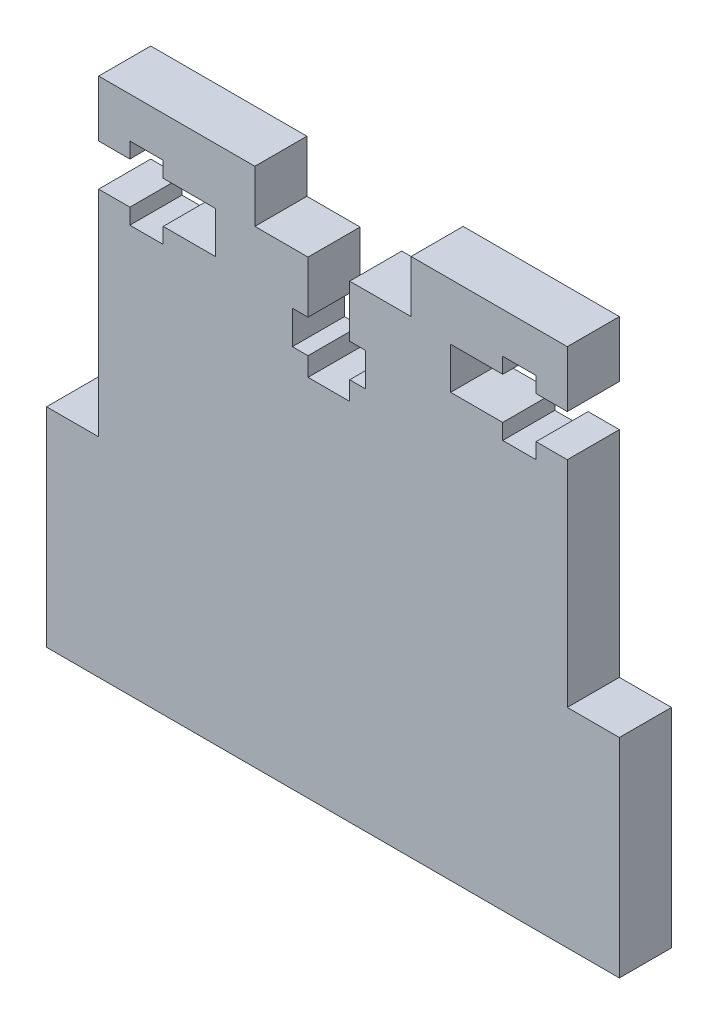
SolidWorks part; units mm, degrees
ref_plane "Front Plane" through (0, 0, 0) normal (0, 0, 1) x (1, 0, 0)
ref_plane "Top Plane" through (0, 0, 0) normal (0, 1, 0) x (1, 0, 0)
ref_plane "Right Plane" through (0, 0, 0) normal (1, 0, 0) x (0, 0, -1)
sketch "Sketch1" plane through (0, 0, 0) normal (0, 0, 1) x (1, 0, 0)
  line L1 (-30, 25) -> (15, 25)
  line L2 (-30, 25) -> (-30, -25)
  line L3 (-30, -25) -> (15, -25)
  line L4 (15, 25) -> (15, -25)
  dimension "D1" = 45
  dimension "D2" = 50
  dimension "D3" = 30
  dimension "D4" = 25
extrude "Boss-Extrude1" add sketch "Sketch1" along normal blind 5
sketch "Sketch5" plane through (0, 0, 5) normal (0, 0, 1) x (1, 0, 0)
  line L14 (-30, 17.6) -> (-13.6039, 17.6) construction
  line L26 (0, 0) -> (-23.656, 0) construction
  line L27 (0, 0) -> (0, 19.5594) construction
  line L28 (-30, 15.6) -> (-30, 19.6)
  line L64 (15, 19.6) -> (12, 19.6)
  line L65 (-27, 15.6) -> (-30, 15.6)
  line L66 (-27, 14.1) -> (-27, 15.6)
  line L67 (-23.8, 14.1) -> (-27, 14.1)
  line L68 (-23.8, 15.6) -> (-23.8, 14.1)
  line L69 (-18.8, 15.6) -> (-23.8, 15.6)
  line L70 (-18.8, 19.6) -> (-18.8, 15.6)
  line L71 (-23.8, 19.6) -> (-18.8, 19.6)
  line L72 (-23.8, 21.1) -> (-23.8, 19.6)
  line L73 (-27, 21.1) -> (-23.8, 21.1)
  line L74 (-27, 19.6) -> (-27, 21.1)
  line L75 (-30, 19.6) -> (-27, 19.6)
  line L78 (15, -25) -> (15, 25) construction
  line L79 (12, 19.6) -> (12, 21.1)
  line L80 (12, 21.1) -> (8.8, 21.1)
  line L81 (8.8, 21.1) -> (8.8, 19.6)
  line L82 (8.8, 19.6) -> (3.8, 19.6)
  line L83 (3.8, 19.6) -> (3.8, 15.6)
  line L84 (3.8, 15.6) -> (8.8, 15.6)
  line L85 (8.8, 15.6) -> (8.8, 14.1)
  line L86 (8.8, 14.1) -> (12, 14.1)
  line L87 (12, 14.1) -> (12, 15.6)
  line L88 (12, 15.6) -> (15, 15.6)
  line L89 (15, 15.6) -> (15, 19.6)
  line L90 (3.8, 17.6) -> (15, 17.6) construction
  dimension "D1" = 4
  dimension "D2" = 2
  dimension "D3" = 1.5
  dimension "D4" = 1.5
  dimension "D5" = 3
  dimension "D6" = 3.2
  dimension "D7" = 5
  dimension "D8" = 3
  dimension "D9" = 3.2
  dimension "D10" = 5
extrude "Cut-Extrude1" cut sketch "Sketch5" against normal blind 5
sketch "Sketch6" plane through (0, 0, 0) normal (0, 0, -1) x (-1, 0, 0)
  line L0 (0, -25) -> (0, 34.8388) construction
  line L1 (-15, -25) -> (-20, -25)
  line L2 (-15, -25) -> (-15, -5)
  line L3 (-15, -5) -> (-20, -5)
  line L4 (-20, -25) -> (-20, -5)
  line L7 (30, -25) -> (35, -25)
  line L8 (30, -25) -> (30, -5)
  line L9 (30, -5) -> (35, -5)
  line L10 (35, -25) -> (35, -5)
  dimension "D1" = 20
  dimension "D2" = 5
  dimension "D3" = 5
  dimension "D4" = 20
extrude "Boss-Extrude2" add sketch "Sketch6" against normal blind 5
sketch "Sketch7" plane through (0, 0, 5) normal (0, 0, 1) x (1, 0, 0)
  line L0 (15, 25) -> (-30, 25) construction
  line L1 (-15, 25) -> (0, 25)
  line L2 (-15, 25) -> (-15, 20)
  line L3 (-15, 20) -> (0, 20)
  line L4 (0, 25) -> (0, 20)
  line L5 (-30, 25) -> (-30, 19.6) construction
  dimension "D1" = 15
  dimension "D2" = 15
  dimension "D3" = 5
extrude "Cut-Extrude2" cut sketch "Sketch7" against normal blind 10
sketch "Sketch8" plane through (0, 0, 5) normal (0, 0, 1) x (1, 0, 0)
  line L0 (-9.8947, 20) -> (-9.8947, 15)
  line L1 (-15, 20) -> (0, 20) construction
  line L2 (-9.8947, 10) -> (-5.8947, 10)
  line L3 (-5.8947, 10) -> (-5.8947, 11.8)
  line L4 (-9.8947, 20) -> (-5.8947, 20)
  line L5 (-9.8947, 15) -> (-11.3947, 15)
  line L6 (-11.3947, 15) -> (-11.3947, 11.8)
  line L7 (-11.3947, 11.8) -> (-9.8947, 11.8)
  line L8 (-9.8947, 11.8) -> (-9.8947, 10)
  line L9 (-5.8947, 15) -> (-4.3947, 15)
  line L10 (-4.3947, 15) -> (-4.3947, 11.8)
  line L11 (-4.3947, 11.8) -> (-5.8947, 11.8)
  line L12 (-5.8947, 15) -> (-5.8947, 20)
  point P4 (-7.8947, 20)
  dimension "D1" = 2
  dimension "D2" = 3.2
  dimension "D3" = 1.5
  dimension "D4" = 1.5
  dimension "D5" = 3.2
  dimension "D6" = 5
  dimension "D7" = 10
extrude "Cut-Extrude3" cut sketch "Sketch8" against normal blind 5
